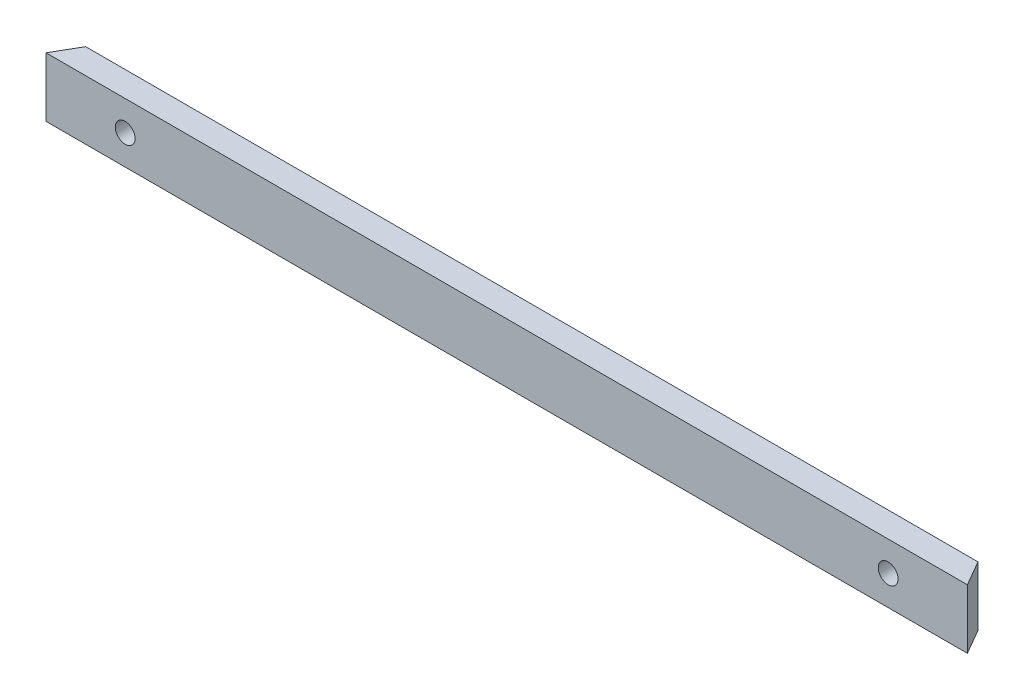
SolidWorks part; units mm, degrees
material "6061 Alloy"
ref_plane "Front Plane" through (0, 0, 0) normal (0, 0, 1) x (1, 0, 0)
ref_plane "Top Plane" through (0, 0, 0) normal (0, 1, 0) x (1, 0, 0)
ref_plane "Right Plane" through (0, 0, 0) normal (1, 0, 0) x (0, 0, -1)
sketch "Sketch1" plane through (0, 0, 0) normal (0, 0, 1) x (1, 0, 0)
  line L5 (0, 0) -> (232.6677, 0)
  line L6 (0, 0) -> (0, 15)
  line L7 (0, 15) -> (232.6677, 15)
  line L8 (232.6677, 0) -> (232.6677, 15)
  dimension "D1" = 232.6677
  dimension "D2" = 15
extrude "Boss-Extrude1" add sketch "Sketch1" against normal blind 6.35 contours L7 L8 L5 L6
sketch "Sketch2" plane through (0, 15, 0) normal (0, 1, 0) x (1, 0, 0)
  line L0 (0, 0) -> (0, 6.35)
  line L1 (0, 6.35) -> (3.6662, 6.35)
  line L3 (0, 0) -> (3.6662, 6.35)
  line L12 (232.6677, 0) -> (229.0015, 6.35)
  line L13 (232.6677, 6.35) -> (229.0015, 6.35)
  line L14 (232.6677, 0) -> (232.6677, 6.35)
extrude "Cut-Extrude1" cut sketch "Sketch2" against normal through all
sketch "Sketch3" plane through (0, 0, 0) normal (0, 0, 1) x (1, 0, 0)
  line L0 (0, 0) -> (0, 15) construction
  line L1 (0, 15) -> (232.6677, 15) construction
  line L2 (232.6677, 0) -> (232.6677, 15) construction
  circle A0 centre (20, 7.5) radius 2.5
  circle A1 centre (212.6677, 7.5) radius 2.5
  dimension "D1" = 20
  dimension "D3" = 20
  dimension "D2" = 7.5
  dimension "D4" = 7.5
extrude "Cut-Extrude2" cut sketch "Sketch3" against normal through all
